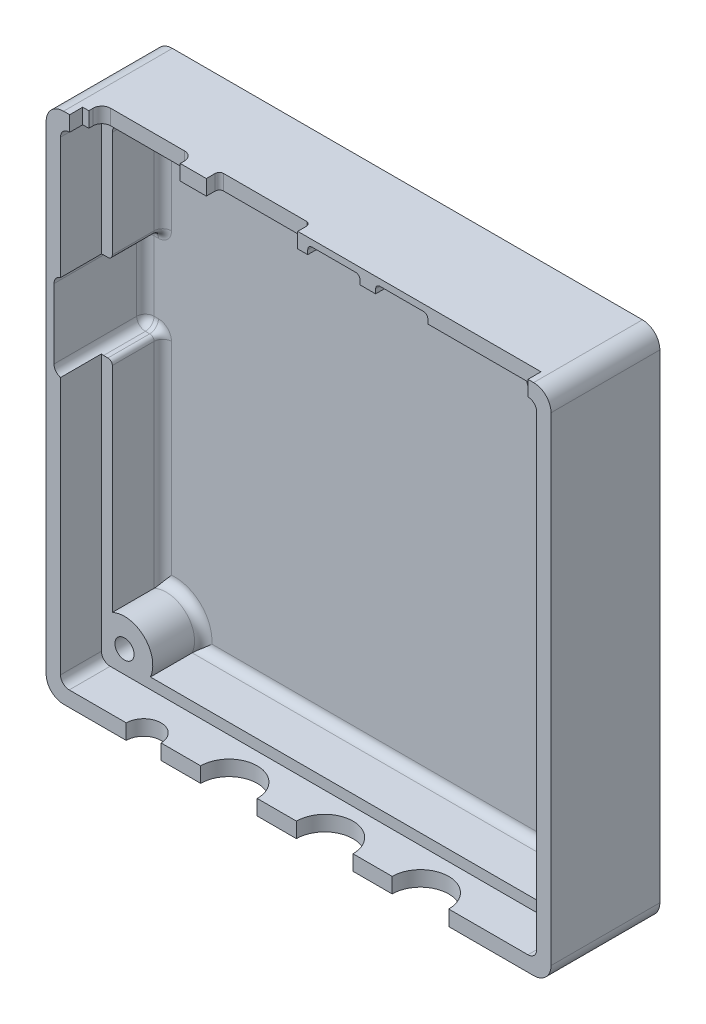
SolidWorks part; units mm, degrees
ref_plane "Front Plane" through (0, 0, 0) normal (0, 0, 1) x (1, 0, 0)
ref_plane "Top Plane" through (0, 0, 0) normal (0, 1, 0) x (1, 0, 0)
ref_plane "Right Plane" through (0, 0, 0) normal (1, 0, 0) x (0, 0, -1)
sketch "Sketch1" plane through (0, 0, 0) normal (0, 0, 1) x (1, 0, 0)
  line L0 (-29, 0) -> (29, 0) construction
  line L1 (-27, -29.5) -> (27, -29.5)
  line L2 (-29, -27.5) -> (-29, 27.5)
  line L3 (-27, 29.5) -> (27, 29.5)
  line L4 (29, -27.5) -> (29, 27.5)
  line L5 (0, -29.5) -> (0, 29.5) construction
  arc A0 (-29, -27.5) -> (-27, -29.5) centre (-27, -27.5) ccw
  arc A1 (27, -29.5) -> (29, -27.5) centre (27, -27.5) ccw
  arc A2 (29, 27.5) -> (27, 29.5) centre (27, 27.5) ccw
  arc A3 (-27, 29.5) -> (-29, 27.5) centre (-27, 27.5) ccw
  point P7 (-28.1524, -26.5589)
  dimension "D1" = 2
  dimension "D2" = 58
  dimension "D3" = 59
extrude "Gehäusekorpus" add sketch "Sketch1" along normal blind 12.5
sketch "Sketch3" plane through (0, 0, 12.5) normal (0, 0, 1) x (1, 0, 0)
  line L0 (0, 26.5) -> (0, -26.5) construction
  line L1 (-25.1, 26.5) -> (21.7213, 26.5)
  line L2 (-26.1, 25.5) -> (-26.1, 13.3)
  line L3 (-21.7213, -26.5) -> (25.1, -26.5)
  line L4 (26.1, 22.267) -> (26.1, -25.5)
  line L5 (26.1, 0) -> (-26.1, 0) construction
  line L6 (-26.1, 2.3) -> (-26.1, -22.267)
  line L7 (-26.6, 12.8) -> (-27.1, 12.8)
  line L9 (-26.6, 2.8) -> (-27.1, 2.8)
  line L10 (-28.1, 11.8) -> (-28.1, 3.8)
  arc A1 (25.1, -26.5) -> (26.1, -25.5) centre (25.1, -25.5) ccw
  arc A3 (-25.1, 26.5) -> (-26.1, 25.5) centre (-25.1, 25.5) ccw
  arc A4 (-28.1, 3.8) -> (-27.1, 2.8) centre (-27.1, 3.8) ccw
  arc A5 (-28.1, 11.8) -> (-27.1, 12.8) centre (-27.1, 11.8) cw
  arc A6 (-26.1, 2.3) -> (-26.6, 2.8) centre (-26.6, 2.3) ccw
  arc A7 (-26.1, 13.3) -> (-26.6, 12.8) centre (-26.6, 13.3) cw
  arc A8 (21.7213, 26.5) -> (26.1, 22.267) centre (24.7, 25.2) ccw
  circle A9 centre (24.7, 25.2) radius 1.1 construction
  arc A10 (-21.7213, -26.5) -> (-26.1, -22.267) centre (-24.7, -25.2) ccw
  circle A11 centre (-24.7, -25.2) radius 1.1 construction
  point P10 (-26.1, -26.5)
  point P18 (-26.1, 26.5)
  point P25 (-28.1, 2.8)
  point P28 (-28.1, 12.8)
  point P31 (-26.1, 2.8)
  dimension "D3" = 46.8213
  dimension "D7" = 1
  dimension "D8" = 0.5
  dimension "D9" = 12.2
  dimension "D12" = 2.2
  dimension "D16" = 2.2
  dimension "D20" = 3.25
  dimension "D21" = 3.25
  dimension "D1" = 53
  dimension "D2" = 52.2
  dimension "D4" = 10
  dimension "D5" = 2
  dimension "D6" = 29.3
  dimension "D10" = 25.2
  dimension "D11" = 24.7
  dimension "D13" = 25.2
  dimension "D14" = 24.7
  dimension "D17" = 24.567
  dimension "D18" = 47.767
  dimension "D19" = 46.8213
extrude "Gehäuseaushöhlung" cut sketch "Sketch3" against normal offset from surface (10.5 mm away) 2 up to face at (0, 0, 0)
sketch "Sketch4" plane through (0, 0, 12.5) normal (0, 0, 1) x (1, 0, 0)
  line L0 (0, 27.75) -> (0, -27.75) construction
  line L1 (-26.35, 27.75) -> (26.35, 27.75)
  line L2 (-27.35, 26.75) -> (-27.35, -26.75)
  line L3 (-26.35, -27.75) -> (26.35, -27.75)
  line L4 (27.35, 26.75) -> (27.35, -26.75)
  arc A0 (-27.35, -26.75) -> (-26.35, -27.75) centre (-26.35, -26.75) ccw
  arc A1 (26.35, -27.75) -> (27.35, -26.75) centre (26.35, -26.75) ccw
  arc A2 (27.35, 26.75) -> (26.35, 27.75) centre (26.35, 26.75) ccw
  arc A3 (-26.35, 27.75) -> (-27.35, 26.75) centre (-26.35, 26.75) ccw
  point P9 (-27.35, -27.75)
  point P14 (27.35, 27.75)
  point P17 (-27.35, 27.75)
  dimension "D3" = 1
  dimension "D1" = 54.7
  dimension "D2" = 55.5
extrude "Platinenhalterung" cut sketch "Sketch4" against normal blind 4.7
sketch "Sketch8" plane through (0, 0, 7.8) normal (0, 0, 1) x (1, 0, 0)
  circle A1 centre (-24.7, -25.2) radius 1.1
  circle A2 centre (24.7, 25.2) radius 1.1
  dimension "D1" = 2.2
  dimension "D2" = 24.7
  dimension "D6" = 2.2
  dimension "D3" = 25.2
  dimension "D4" = 24.7
  dimension "D5" = 25.2
extrude "Schraublöcher" cut sketch "Sketch8" against normal through all
sketch "Sketch9" plane through (0, 0, 0) normal (0, 0, 1) x (1, 0, 0)
  line L0 (26.35, 27.75) -> (-26.35, 27.75) construction
  line L1 (27.1826, 25.2) -> (25.9413, 27.35)
  line L2 (25.9413, 27.35) -> (23.4587, 27.35)
  line L3 (23.4587, 27.35) -> (22.2174, 25.2)
  line L4 (22.2174, 25.2) -> (23.4587, 23.05)
  line L5 (23.4587, 23.05) -> (25.9413, 23.05)
  line L6 (25.9413, 23.05) -> (27.1826, 25.2)
  line L7 (-22.2174, -25.2) -> (-23.4587, -23.05)
  line L8 (-23.4587, -23.05) -> (-25.9413, -23.05)
  line L9 (-25.9413, -23.05) -> (-27.1826, -25.2)
  line L10 (-27.1826, -25.2) -> (-25.9413, -27.35)
  line L11 (-25.9413, -27.35) -> (-23.4587, -27.35)
  line L12 (-23.4587, -27.35) -> (-22.2174, -25.2)
  line L13 (-26.35, -27.75) -> (26.35, -27.75) construction
  circle A0 centre (24.7, 25.2) radius 2.15 construction
  circle A1 centre (-24.7, -25.2) radius 2.15 construction
  dimension "D1" = 4.3
  dimension "D2" = 4.3
extrude "Schraubenmutter_Ausnehmungen" cut sketch "Sketch9" along normal blind 3
sketch "Sketch10" plane through (0, -29.5, 0) normal (0, -1, 0) x (1, 0, 0)
  line L0 (-27, 12.5) -> (27, 12.5) construction
  line L1 (-27.1, 12.5) -> (27.1, 12.5) construction
  circle A0 centre (-8, 12.5) radius 3.25
  circle A1 centre (3, 12.5) radius 3.25
  circle A2 centre (14, 12.5) radius 3.25
  circle A3 centre (-17.8, 12.5) radius 2
  dimension "D1" = 6.5
  dimension "D2" = 6.5
  dimension "D3" = 6.5
  dimension "D4" = 4
  dimension "D5" = 11
  dimension "D6" = 11
  dimension "D7" = 9.8
  dimension "D8" = 54.2
  dimension "D9" = 9.3
  dimension "D10" = 12.5
  dimension "D11" = 27.1
extrude "Button_Ausnehmungen" cut sketch "Sketch10" against normal blind 3
sketch "Skizze1" plane through (0, 29.5, 0) normal (0, 1, 0) x (1, 0, 0)
  line L0 (27, -12.5) -> (-27, -12.5) construction
  line L1 (-15.1, -12.5) -> (-25.6, -12.5)
  line L2 (-15.1, -12.5) -> (-15.1, -10.5)
  line L3 (-16.1, -9.5) -> (-24.6, -9.5)
  line L4 (-25.6, -12.5) -> (-25.6, -10.5)
  line L5 (-27, -12.5) -> (-27, 0) construction
  line L6 (-12.1, -12.5) -> (-1.6, -12.5)
  line L7 (-12.1, -12.5) -> (-12.1, -10)
  line L8 (-11.6, -9.5) -> (-2.1, -9.5)
  line L9 (-1.6, -12.5) -> (-1.6, -10)
  arc A0 (-15.1, -10.5) -> (-16.1, -9.5) centre (-16.1, -10.5) ccw
  arc A1 (-24.6, -9.5) -> (-25.6, -10.5) centre (-24.6, -10.5) ccw
  arc A2 (-1.6, -10) -> (-2.1, -9.5) centre (-2.1, -10) ccw
  arc A3 (-11.6, -9.5) -> (-12.1, -10) centre (-11.6, -10) ccw
  point P16 (-15.1, -9.5)
  point P19 (-25.6, -9.5)
  point P22 (-1.6, -9.5)
  point P25 (-12.1, -9.5)
  dimension "D7" = 1
  dimension "D8" = 0.5
  dimension "D1" = 10.5
  dimension "D2" = 1.4
  dimension "D3" = 3
  dimension "D4" = 10.5
  dimension "D5" = 3
  dimension "D6" = 1.6
extrude "Schnitt-Linear austragen1" cut sketch "Skizze1" against normal blind 10
sketch "Skizze2" plane through (0, 0, 12.5) normal (0, 0, 1) x (1, 0, 0)
  line L0 (-25.6, 29.5) -> (-27, 29.5) construction
  line L1 (26.35, 27.75) -> (-26.3, 27.75)
  line L2 (26.35, 27.75) -> (26.35, 29.5)
  line L3 (26.35, 29.5) -> (-26.3, 29.5)
  line L4 (-26.3, 27.75) -> (-26.3, 29.5)
extrude "Schnitt-Linear austragen2" cut sketch "Skizze2" against normal blind 1.5
sketch "Skizze3" plane through (0, 0, 11) normal (0, 0, 1) x (1, 0, 0)
  line L0 (-1.6, 27.75) -> (26.35, 27.75) construction
  line L1 (-0.45, 27.75) -> (5.55, 27.75)
  line L2 (-0.45, 27.75) -> (-0.45, 28.75)
  line L3 (-0.45, 28.75) -> (5.55, 28.75)
  line L4 (5.55, 27.75) -> (5.55, 28.75)
  line L5 (26.35, 27.75) -> (-26.35, 27.75) construction
  line L6 (7.35, 27.75) -> (13.35, 27.75)
  line L7 (7.35, 27.75) -> (7.35, 28.75)
  line L8 (7.35, 28.75) -> (13.35, 28.75)
  line L9 (13.35, 27.75) -> (13.35, 28.75)
  line L10 (26.35, 27.75) -> (26.35, 29.5) construction
  point P14 (13.35, 28.25)
  dimension "D1" = 13
  dimension "D2" = 6
  dimension "D3" = 6
  dimension "D4" = 1.8
  dimension "D5" = 1
  dimension "D6" = 1
extrude "Schnitt-Linear austragen3" cut sketch "Skizze3" against normal blind 1.5
fillet "Verrundung1" radius 0.5 10 edges at (-0.45, 28.75, 10.25) (7.35, 28.75, 10.25) (13.35, 28.75, 10.25) (5.55, 28.75, 10.25) (2.55, 28.75, 9.5) (10.35, 28.75, 9.5) (5.55, 28.25, 9.5) (13.35, 28.25, 9.5) (7.35, 28.25, 9.5) (-0.45, 28.25, 9.5)
fillet "Verrundung2" radius 1 16 edges at (-26.1, -9.9835, 2) (-26.2464, 2.6536, 2) (-26.85, 2.8, 2) (-27.8071, 3.0929, 2) (-28.1, 7.8, 2) (-27.8071, 12.5071, 2) (-26.85, 12.8, 2) (-26.2464, 12.9464, 2) (-26.1, 19.4, 2) (-25.8071, 26.2071, 2) (-1.6893, 26.5, 2) (22.4411, 22.8634, 2) (26.1, -1.6165, 2) (25.8071, -26.2071, 2) (1.6893, -26.5, 2) (-22.4411, -22.8634, 2)
equation "\"D151.000000mm\"=51"
equation "\"D250.000000mm\"=50"
